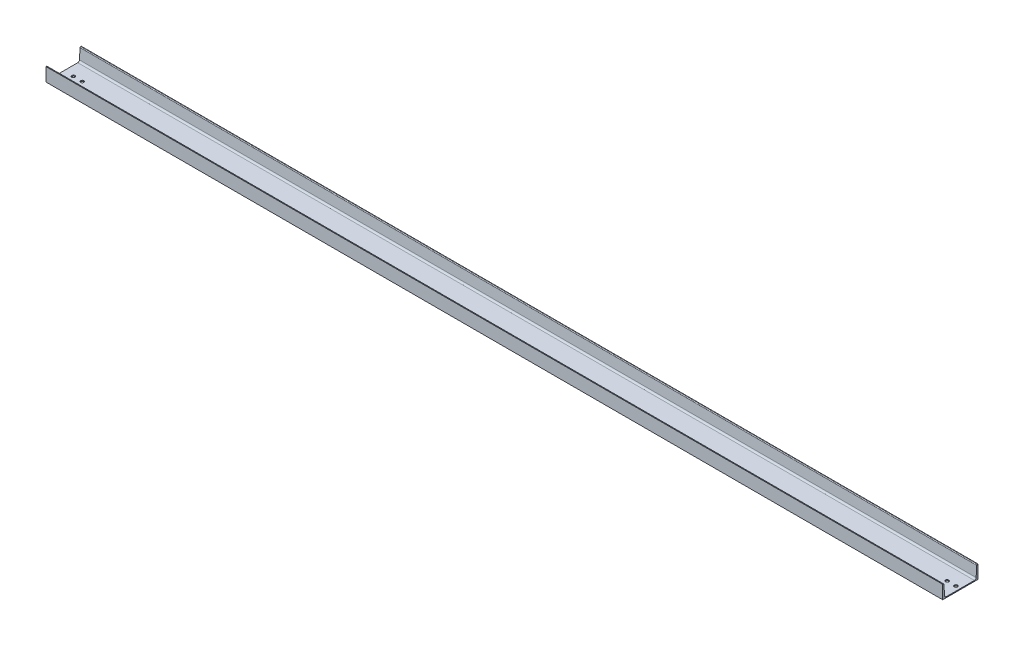
SolidWorks part; units mm, degrees
material "Простая углеродистая сталь"
ref_plane "Спереди" through (0, 0, 0) normal (0, 0, 1) x (1, 0, 0)
ref_plane "Сверху" through (0, 0, 0) normal (0, 1, 0) x (1, 0, 0)
ref_plane "Справа" through (0, 0, 0) normal (1, 0, 0) x (0, 0, -1)
sketch "Эскиз1" plane through (0, 0, 0) normal (0, 0, 1) x (1, 0, 0)
  line L0 (0, 0) -> (5080, 0)
  dimension "D1" = 5080
other "Швеллеры гост 8240-89 с уклоном 20(1)"
ref_plane "Плоскость1" through (0, 0, 0) normal (1, 0, 0) x (0, 1, 0)
sketch "Sketch1" plane through (0, 0, 0) normal (1, 0, 0) x (0, 1, 0)
  line L0 (-15.5, -79.9289) -> (-15.5, 79.9289)
  line L1 (-20.7, 100) -> (-20.7, -100)
  line L2 (55.3, -96.8912) -> (55.3, -100)
  line L3 (-6.569, 89.4119) -> (51.5396, 92.8984)
  line L4 (-20.7, 100) -> (55.3, 100)
  line L5 (-20.7, -100) -> (55.3, -100)
  line L6 (-6.569, -89.4119) -> (51.5396, -92.8984)
  line L7 (55.3, 96.8912) -> (55.3, 100)
  line L8 (0, 0) -> (-20.7, 0) construction
  line L9 (0, 0) -> (55.3, 0) construction
  line L10 (-6.569, -89.4119) -> (-6.569, -92.8984) construction
  line L11 (-6.569, -92.8984) -> (51.5396, -92.8984) construction
  arc A0 (51.5396, -92.8984) -> (55.3, -96.8912) centre (51.3, -96.8912) cw
  arc A1 (-15.5, 79.9289) -> (-6.569, 89.4119) centre (-6, 79.9289) cw
  arc A2 (51.5396, 92.8984) -> (55.3, 96.8912) centre (51.3, 96.8912) ccw
  arc A3 (-15.5, -79.9289) -> (-6.569, -89.4119) centre (-6, -79.9289) ccw
  point P1 (19.9, -91)
  point P4 (19.9, 91)
  point P14 (0, 0)
  point P17 (-15.5, 0)
  point P19 (0, 0)
  dimension "R" = 9.5
  dimension "_r" = 4
  dimension "t" = 9
  dimension "D1" = 58.1085
  dimension "(b-S)/2" = 35.4
  dimension "D2" = 3.4865
  dimension "b" = 76
  dimension "h" = 200
  dimension "S" = 5.2
  dimension "Z0" = 20.7
sketch "Эскиз3" plane through (0, -20.7, 0) normal (0, -1, 0) x (1, 0, 0)
  line L0 (2540, 100) -> (2540, 0) construction
  line L1 (5080, 100) -> (0, 100) construction
  line L2 (1500, 100) -> (1500, -169.4871) construction
  line L3 (0, 100) -> (0, -100) construction
  line L4 (5080, 100) -> (5080, -100) construction
  line L5 (5080, -100) -> (0, -100) construction
  circle A12 centre (55, 0) radius 9
  circle A13 centre (105, 0) radius 9
  circle A18 centre (5005, 0) radius 9
  circle A19 centre (5055, 0) radius 9
  dimension "D2" = 18
  dimension "D9" = 50
  dimension "D13" = 25
  dimension "D1" = 1500
  dimension "D3" = 100
  dimension "D7" = 55
  dimension "D8" = 2
  dimension "D12" = 2
extrude "Вырез-Вытянуть1" cut sketch "Эскиз3" against normal blind 10
equation "\"(b-S)/2@Sketch1\" = (\"b@Sketch1\"-\"S@Sketch1\")/2"
equation "\"D2@Sketch1\" = \"D1@Sketch1\"*0.06"
